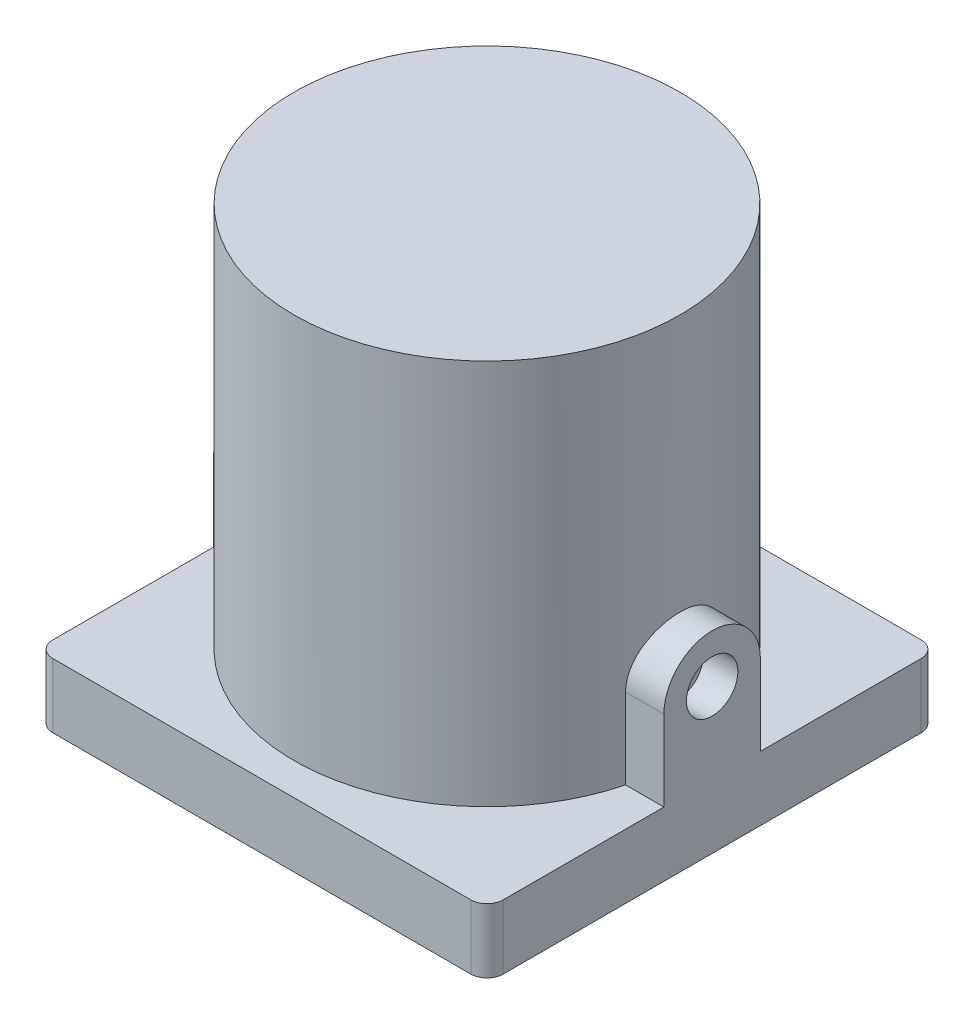
SolidWorks part; units mm, degrees
ref_plane "Front Plane" through (0, 0, 0) normal (0, 0, 1) x (1, 0, 0)
ref_plane "Top Plane" through (0, 0, 0) normal (0, 1, 0) x (1, 0, 0)
ref_plane "Right Plane" through (0, 0, 0) normal (1, 0, 0) x (0, 0, -1)
sketch "Sketch1" plane through (0, 0, 0) normal (0, 1, 0) x (1, 0, 0)
  line L1 (-6.5, 7) -> (6.5, 7)
  line L2 (-7, 6.5) -> (-7, -6.5)
  line L3 (-6.5, -7) -> (6.5, -7)
  line L4 (7, 6.5) -> (7, -6.5)
  arc A0 (-6.5, 7) -> (-7, 6.5) centre (-6.5, 6.5) ccw
  arc A1 (-7, -6.5) -> (-6.5, -7) centre (-6.5, -6.5) ccw
  arc A2 (6.5, -7) -> (7, -6.5) centre (6.5, -6.5) ccw
  arc A3 (6.5, 7) -> (7, 6.5) centre (6.5, 6.5) cw
  point P4 (0, 7)
  point P5 (7, 0)
  point P6 (0, 0)
  point P8 (0, 0)
  point P11 (-7, 7)
  point P16 (7, -7)
  point P19 (7, 7)
  dimension "D3" = 0.5
  dimension "D1" = 14
  dimension "D2" = 14
extrude "Boss-Extrude1" add sketch "Sketch1" along normal blind 2
sketch "Sketch2" plane through (-7, 0, 0) normal (-1, 0, 0) x (0, 0, 1)
  line L0 (-1.5, 4.5) -> (-1.5, 2)
  line L1 (-6.5, 2) -> (6.5, 2) construction
  line L2 (-1.5, 2) -> (1.5, 2)
  line L3 (1.5, 2) -> (1.5, 4.5)
  line L4 (-6.5, 0) -> (6.5, 0) construction
  arc A0 (-1.5, 4.5) -> (1.5, 4.5) centre (0, 4.5) cw
  point P9 (0, 0)
  point P10 (0, 0)
  dimension "D1" = 4.5
  dimension "D2" = 3
extrude "Boss-Extrude2" add sketch "Sketch2" against normal through all
sketch "Sketch3" plane through (-7, 0, 0) normal (-1, 0, 0) x (0, 0, 1)
  circle A0 centre (0, 4.5) radius 0.8
  arc A1 (1.5, 4.5) -> (-1.5, 4.5) centre (0, 4.5) ccw construction
  dimension "D1" = 1.6
extrude "Cut-Extrude1" cut sketch "Sketch3" against normal through all
sketch "Sketch4" plane through (0, 2, 0) normal (0, 1, 0) x (1, 0, 0)
  circle A0 centre (0, 0) radius 6
  dimension "D1" = 12
extrude "Boss-Extrude3" add sketch "Sketch4" along normal offset from surface (12 mm away) 14 up to face at (0, 0, 0)
